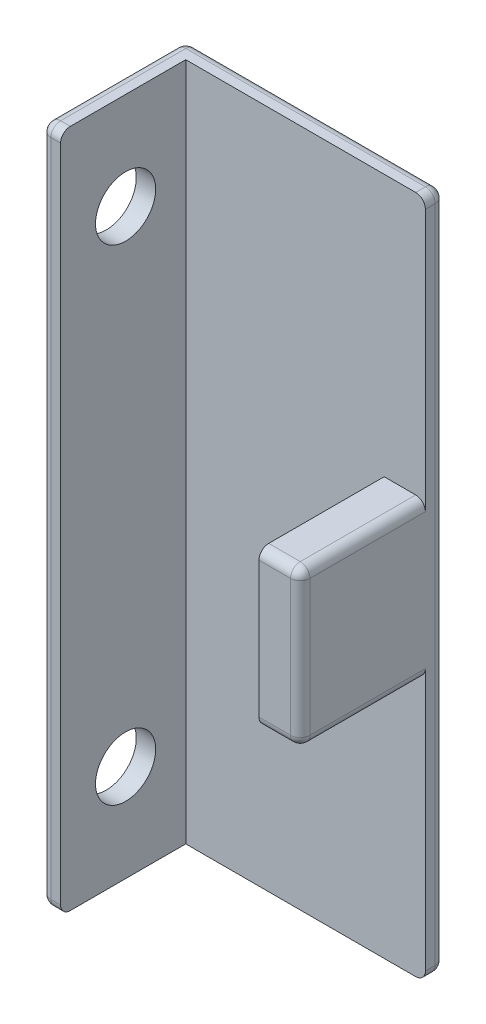
SolidWorks part; units mm, degrees
ref_plane "Front Plane" through (0, 0, 0) normal (0, 0, 1) x (1, 0, 0)
ref_plane "Top Plane" through (0, 0, 0) normal (0, 1, 0) x (1, 0, 0)
ref_plane "Right Plane" through (0, 0, 0) normal (1, 0, 0) x (0, 0, -1)
sketch "Sketch1" plane through (0, 0, 0) normal (0, 0, 1) x (1, 0, 0)
  line L1 (0, 0) -> (26.7, 0)
  line L2 (0, 0) -> (0, 70)
  line L3 (0, 70) -> (26.7, 70)
  line L4 (26.7, 0) -> (26.7, 70)
  dimension "D1" = 70
  dimension "D2" = 26.7
extrude "Boss-Extrude1" add sketch "Sketch1" along normal blind 2
sketch "Sketch2" plane through (0, 0, 2) normal (0, 0, 1) x (1, 0, 0)
  line L0 (0, 0) -> (26.7, 0) construction
  line L1 (0, 70) -> (2, 70)
  line L2 (0, 70) -> (0, 0)
  line L3 (0, 0) -> (2, 0)
  line L4 (2, 70) -> (2, 0)
  line L6 (26.7, 70) -> (24.7, 70)
  line L7 (26.7, 70) -> (26.7, 0)
  line L8 (26.7, 0) -> (24.7, 0)
  line L9 (24.7, 70) -> (24.7, 0)
  dimension "D1" = 2
extrude "Boss-Extrude2" add sketch "Sketch2" along normal blind 12.9
sketch "Sketch3" plane through (0, 0, 0) normal (-1, 0, 0) x (0, 0, 1)
  line L1 (2, 0) -> (2, 70) construction
  line L3 (14.9, 0) -> (0, 0) construction
  circle A0 centre (8.2, 10) radius 3.1
  dimension "D1" = 6.2
  dimension "D2" = 6.2
  dimension "D3" = 10
extrude "Cut-Extrude1" cut sketch "Sketch3" against normal through all
ref_plane "Plane1" through (0, 35, 0) normal (0, 1, 0) x (1, 0, 0)
mirror "Mirror1" about plane through (0, 35, 0) normal (0, 1, 0) of "Cut-Extrude1"
fillet "Fillet1" radius 1 1 edges at (13.35, 70, 0)
fillet "Fillet2" radius 1 3 edges at (0, 34.5, 0) (0, 69.7071, 0.2929) (0, 70, 7.95)
fillet "Fillet3" radius 1 3 edges at (26.7, 34.5, 0) (26.7, 69.7071, 0.2929) (26.7, 70, 7.95)
fillet "Fillet6" radius 1 5 edges at (13.35, 0, 0) (0.2929, 0, 0.2929) (26.7, 0, 7.95) (0, 0, 7.95) (26.4071, 0, 0.2929)
fillet "Fillet7" radius 1 5 edges at (1.5, 70, 14.9) (0, 35, 14.9) (0.2929, 69.7071, 14.9) (1.5, 0, 14.9) (0.2929, 0.2929, 14.9)
fillet "Fillet8" radius 1 5 edges at (25.2, 0, 14.9) (25.2, 70, 14.9) (26.4071, 69.7071, 14.9) (26.7, 35, 14.9) (26.4071, 0.2929, 14.9)
sketch "Sketch5" plane through (24.7, 0, 0) normal (-1, 0, 0) x (0, 0, 1)
  line L0 (14.9, 69) -> (14.9, 1) construction
  line L1 (2, 70) -> (14.9, 70)
  line L2 (2, 70) -> (2, 43)
  line L3 (2, 43) -> (14.9, 43)
  line L4 (14.9, 70) -> (14.9, 43)
  line L6 (2, 0) -> (14.9, 0)
  line L7 (2, 0) -> (2, 27)
  line L8 (2, 27) -> (14.9, 27)
  line L9 (14.9, 0) -> (14.9, 27)
  dimension "D1" = 27
  dimension "D2" = 27
extrude "Cut-Extrude2" cut sketch "Sketch5" against normal up to surface (2 mm away) contours L2 L1 L4 L3 | L7 L6 L9 L8 up to face at (26.7, 60, 11.3)
sketch "Sketch6" plane through (24.7, 0, 0) normal (-1, 0, 0) x (0, 0, 1)
  line L1 (2, 43) -> (14.9, 43)
  line L2 (2, 43) -> (2, 27)
  line L3 (2, 27) -> (14.9, 27)
  line L4 (14.9, 43) -> (14.9, 27)
extrude "Boss-Extrude3" add sketch "Sketch6" along normal blind 2.25
fillet "Fillet11" radius 1 3 edges at (24.075, 27, 14.9) (26.7, 27, 7.95) (26.4071, 27, 14.6071)
fillet "Fillet12" radius 1 3 edges at (24.075, 43, 14.9) (26.4071, 43, 14.6071) (26.7, 43, 7.95)
